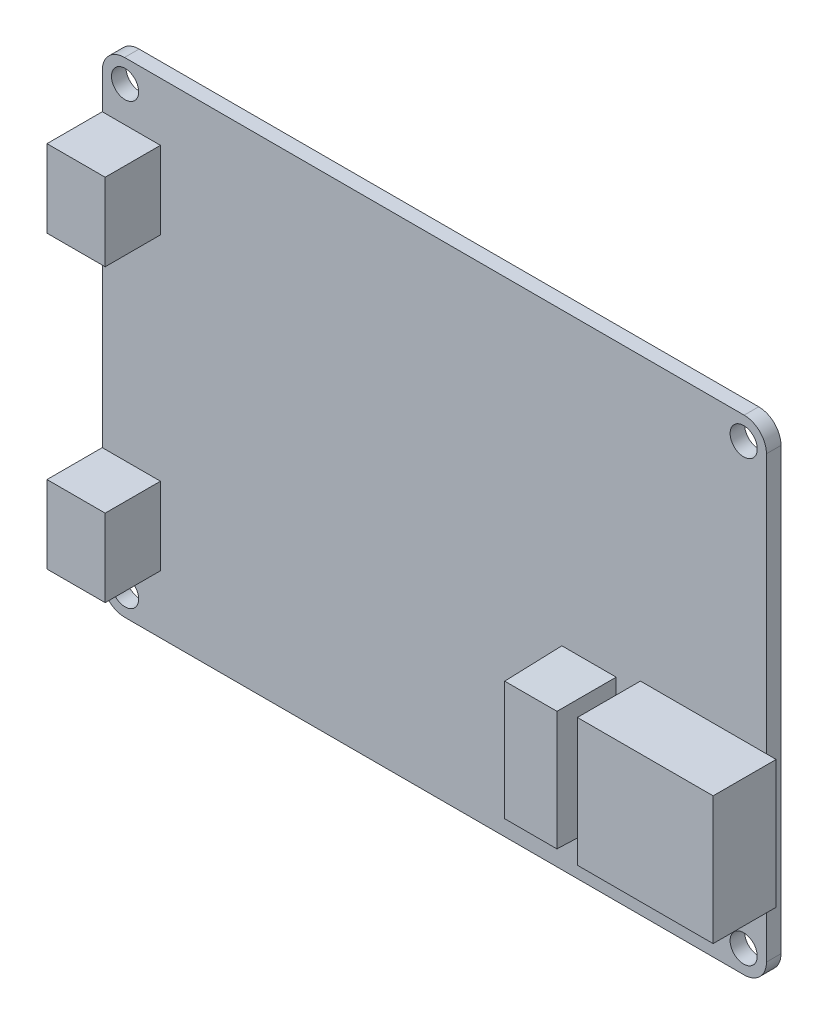
SolidWorks part; units mm, degrees
ref_plane "前基準面" through (0, 0, 0) normal (0, 0, 1) x (1, 0, 0)
ref_plane "上基準面" through (0, 0, 0) normal (0, 1, 0) x (1, 0, 0)
ref_plane "右基準面" through (0, 0, 0) normal (1, 0, 0) x (0, 0, -1)
sketch "草圖1" plane through (0, 0, 0) normal (0, 0, 1) x (1, 0, 0)
  line L1 (25.8893, 80.9435) -> (89.7893, 80.9435)
  line L2 (23.5893, 78.6435) -> (23.5893, 33.2435)
  line L3 (25.8893, 30.9435) -> (89.7893, 30.9435)
  line L4 (92.0893, 78.6435) -> (92.0893, 33.2435)
  line L5 (101.6393, 85.9435) -> (14.0393, 85.9435) construction
  line L6 (102.3393, 72.1272) -> (102.3393, 85.2435) construction
  line L7 (13.3393, 85.2435) -> (13.3393, 72.8435) construction
  line L8 (27.8393, 16.3435) -> (33.8393, 16.3435) construction
  line L9 (13.7314, 4.7435) -> (101.6393, 4.7435) construction
  circle A2 centre (25.9393, 78.5935) radius 1.4
  circle A3 centre (25.9393, 33.2935) radius 1.4
  circle A4 centre (89.7393, 33.2935) radius 1.4
  circle A5 centre (89.7393, 78.5935) radius 1.4
  arc A6 (25.8893, 80.9435) -> (23.5893, 78.6435) centre (25.8893, 78.6435) ccw
  arc A7 (23.5893, 33.2435) -> (25.8893, 30.9435) centre (25.8893, 33.2435) ccw
  arc A8 (89.7893, 30.9435) -> (92.0893, 33.2435) centre (89.7893, 33.2435) ccw
  arc A9 (89.7893, 80.9435) -> (92.0893, 78.6435) centre (89.7893, 78.6435) cw
  point P16 (23.5893, 80.9435)
  point P19 (23.5893, 30.9435)
  point P24 (92.0893, 80.9435)
  dimension "D1" = 2.8
  dimension "D2" = 2.8
  dimension "D4" = 2.8
  dimension "D5" = 2.8
  dimension "D10" = 2.35
  dimension "D11" = 2.35
  dimension "D12" = 2.35
  dimension "D13" = 2.35
  dimension "D15" = 45.3
  dimension "D16" = 2.3
  dimension "D3" = 50
  dimension "D6" = 2.35
  dimension "D7" = 2.35
  dimension "D8" = 2.35
  dimension "D9" = 68.5
  dimension "D14" = 2.35
  dimension "D17" = 10.25
  dimension "D18" = 5
  dimension "D19" = 10.25
  dimension "D20" = 14.6
  dimension "D21" = 26.2
extrude "填料-伸長1" add sketch "草圖1" along normal blind 1.5
sketch "草圖2" plane through (0, 0, 1.5) normal (0, 0, 1) x (1, 0, 0)
  line L0 (25.8893, 30.9435) -> (89.7893, 30.9435) construction
  line L1 (79.0893, 51.8435) -> (93.0893, 51.8435)
  line L2 (79.0893, 51.8435) -> (79.0893, 38.6435)
  line L3 (79.0893, 38.6435) -> (93.0893, 38.6435)
  line L4 (93.0893, 51.8435) -> (93.0893, 38.6435)
  line L5 (92.0893, 33.2435) -> (92.0893, 78.6435) construction
  dimension "D1" = 14
  dimension "D2" = 13.2
  dimension "D3" = 7.7
  dimension "D4" = 1
extrude "填料-伸長2" add sketch "草圖2" along normal blind 6.5
sketch "草圖3" plane through (0, 0, 1.5) normal (0, 0, 1) x (1, 0, 0)
  line L0 (79.0893, 51.8435) -> (79.0893, 38.6435) construction
  line L1 (76.5893, 50.9435) -> (70.9893, 50.9435)
  line L2 (76.5893, 50.9435) -> (76.5893, 38.4435)
  line L3 (76.5893, 38.4435) -> (70.9893, 38.4435)
  line L4 (70.9893, 50.9435) -> (70.9893, 38.4435)
  line L5 (25.8893, 30.9435) -> (89.7893, 30.9435) construction
  dimension "D1" = 5.6
  dimension "D2" = 12.5
  dimension "D3" = 2.5
  dimension "D4" = 7.5
extrude "填料-伸長3" add sketch "草圖3" along normal blind 6 draft 1
sketch "草圖4" plane through (0, 0, 1.5) normal (0, 0, 1) x (1, 0, 0)
  line L0 (89.7893, 80.9435) -> (25.8893, 80.9435) construction
  line L1 (23.5893, 74.9435) -> (29.5893, 74.9435)
  line L2 (23.5893, 74.9435) -> (23.5893, 66.9435)
  line L3 (23.5893, 66.9435) -> (29.5893, 66.9435)
  line L4 (29.5893, 74.9435) -> (29.5893, 66.9435)
  line L5 (23.5893, 44.9435) -> (29.5893, 44.9435)
  line L6 (23.5893, 44.9435) -> (23.5893, 36.9435)
  line L7 (23.5893, 36.9435) -> (29.5893, 36.9435)
  line L8 (29.5893, 44.9435) -> (29.5893, 36.9435)
  line L9 (25.8893, 30.9435) -> (89.7893, 30.9435) construction
  line L11 (23.5893, 78.6435) -> (23.5893, 33.2435) construction
  dimension "D1" = 8
  dimension "D2" = 6
  dimension "D3" = 6
  dimension "D4" = 8
  dimension "D5" = 6
  dimension "D6" = 6
extrude "填料-伸長4" add sketch "草圖4" along normal blind 5.7
